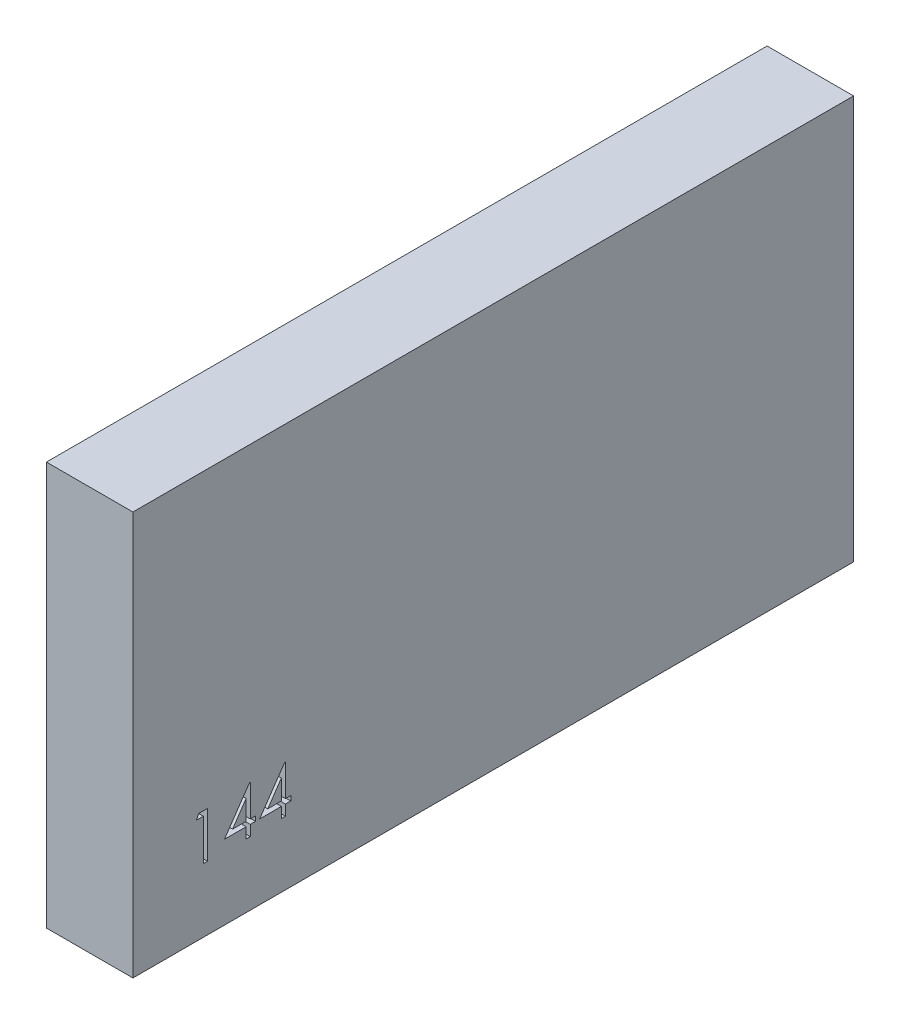
SolidWorks part; units mm, degrees
material "Acrylic (Medium-high impact)"
ref_plane "Front Plane" through (0, 0, 0) normal (0, 0, 1) x (1, 0, 0)
ref_plane "Top Plane" through (0, 0, 0) normal (0, 1, 0) x (1, 0, 0)
ref_plane "Right Plane" through (0, 0, 0) normal (1, 0, 0) x (0, 0, -1)
sketch "Sketch1" plane through (0, 0, 0) normal (1, 0, 0) x (0, 0, -1)
  line L1 (-25, 14) -> (25, 14)
  line L2 (-25, 14) -> (-25, -14)
  line L3 (-25, -14) -> (25, -14)
  line L4 (25, 14) -> (25, -14)
  line L5 (-25, 14) -> (25, -14) construction
  line L6 (-25, -14) -> (25, 14) construction
  point P0 (0, 0)
  dimension "D1" = 50
  dimension "D2" = 28
extrude "Boss-Extrude1" add sketch "Sketch1" along normal blind 6
sketch "Sketch2" plane through (6, 0, 0) normal (1, 0, 0) x (0, 0, -1)
  text T0 "144"
extrude "Cut-Extrude1" cut sketch "Sketch2" against normal blind 1
